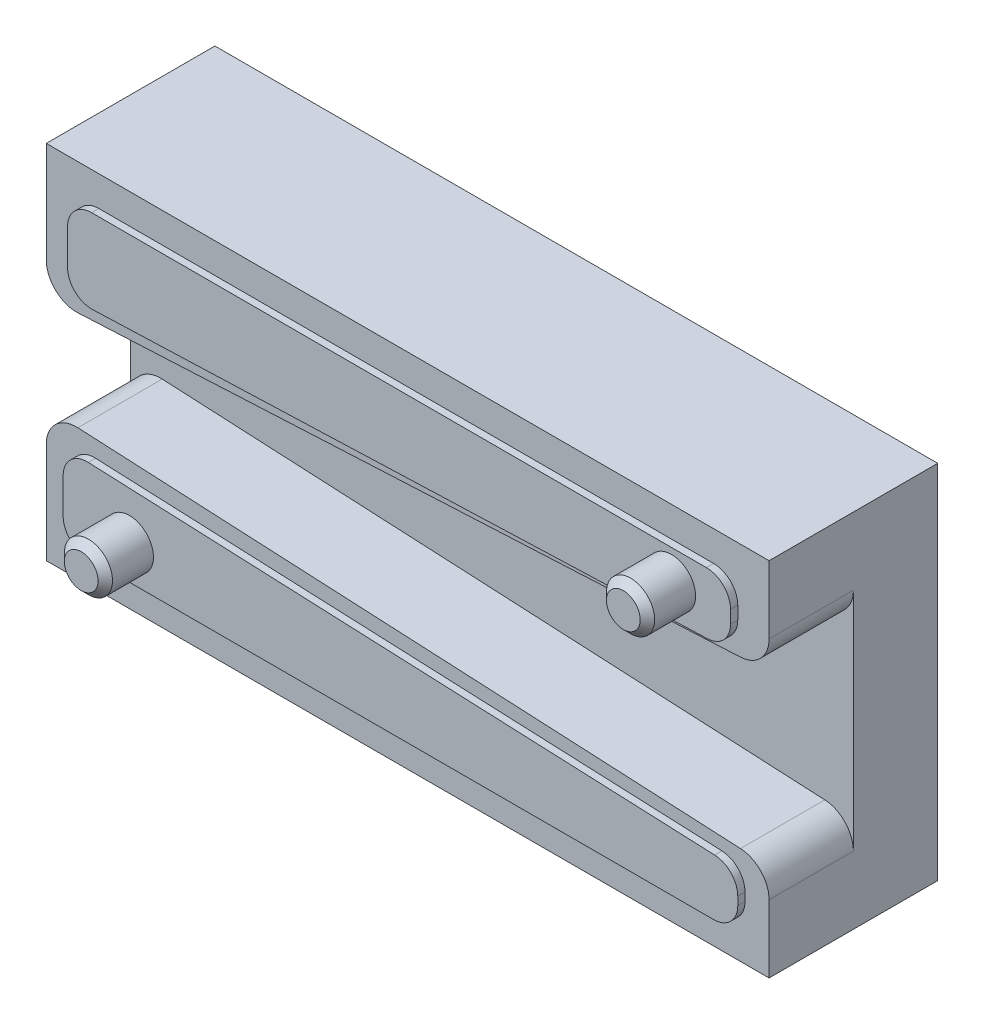
SolidWorks part; units mm, degrees
ref_plane "Front Plane" through (0, 0, 0) normal (0, 0, 1) x (1, 0, 0)
ref_plane "Top Plane" through (0, 0, 0) normal (0, 1, 0) x (1, 0, 0)
ref_plane "Right Plane" through (0, 0, 0) normal (1, 0, 0) x (0, 0, -1)
sketch "Sketch1" plane through (0, 0, 0) normal (0, 0, 1) x (1, 0, 0)
  line L1 (0, 0) -> (-76.2, 0)
  line L2 (0, 0) -> (0, -38.1)
  line L3 (0, -38.1) -> (-76.2, -38.1)
  line L4 (-76.2, 0) -> (-76.2, -38.1)
  dimension "D1" = 38.1
  dimension "D2" = 76.2
extrude "Boss-Extrude1" add sketch "Sketch1" along normal blind 17.78
sketch "Sketch2" plane through (0, 0, 17.78) normal (0, 0, 1) x (1, 0, 0)
  line L0 (-76.2, -24.13) -> (-76.2, -13.97)
  line L1 (-76.2, 0) -> (-76.2, -38.1) construction
  line L2 (0, -27.94) -> (0, -10.16)
  line L3 (0, -38.1) -> (0, 0) construction
  line L4 (-76.2, -13.97) -> (0, -10.16)
  line L5 (-76.2, -24.13) -> (0, -27.94)
  point P5 (-76.2, -19.05)
  point P10 (0, -19.05)
  dimension "D1" = 5.08
  dimension "D2" = 8.89
extrude "Cut-Extrude1" cut sketch "Sketch2" against normal blind 8.89
fillet "Fillet1" radius 3.175 4 edges at (-76.2, -24.13, 13.335) (-76.2, -13.97, 13.335) (0, -27.94, 13.335) (0, -10.16, 13.335)
sketch "Sketch3" plane through (0, 0, 17.78) normal (0, 0, 1) x (1, 0, 0)
  line L0 (-76.2, -38.1) -> (0, -38.1) construction
  line L2 (-76.2, -19.05) -> (0, -19.05) construction
  line L3 (-76.2, -10.6323) -> (-76.2, -27.4677) construction
  line L4 (0, -30.9602) -> (0, -7.1398) construction
  line L5 (-38.1, -38.1) -> (-38.1, 0) construction
  line L6 (0, 0) -> (-76.2, 0) construction
  line L7 (-9.525, -6.35) -> (-9.525, 0) construction
  circle A1 centre (-9.525, -6.35) radius 2.54
  circle A2 centre (-66.675, -31.369) radius 2.54
  dimension "D1" = 5.08
  dimension "D2" = 5.08
  dimension "D4" = 6.35
extrude "Boss-Extrude2" add sketch "Sketch3" along normal offset from surface (5.842 mm away) 23.622 up to face at (-38.1, -19.05, 0)
chamfer "Chamfer1" distance 0.762 angle 45 2 edges at (-12.065, -6.35, 23.622) (-69.215, -31.369, 23.622)
sketch "Sketch4" plane through (0, 0, 17.78) normal (0, 0, 1) x (1, 0, 0)
  line L0 (-73.66, -26.035) -> (-2.54, -29.083)
  line L1 (-2.54, -29.083) -> (-2.54, -34.925)
  line L2 (-2.54, -34.925) -> (-73.66, -34.925)
  line L3 (-73.66, -34.925) -> (-73.66, -26.035)
  line L6 (-76.2, -38.1) -> (0, -38.1) construction
  dimension "D1" = 3.175
  dimension "D4" = 8.89
  dimension "D5" = 5.842
extrude "Boss-Extrude3" add sketch "Sketch4" along normal blind 0.762
fillet "Fillet2" radius 2.54 4 edges at (-73.66, -34.925, 18.161) (-73.66, -26.035, 18.161) (-2.54, -29.083, 18.161) (-2.54, -34.925, 18.161)
sketch "Sketch5" plane through (0, 0, 17.78) normal (0, 0, 1) x (1, 0, 0)
  line L1 (-73.1926, -3.175) -> (-3.302, -3.175)
  line L2 (-73.1926, -3.175) -> (-73.1926, -12.065)
  line L3 (-73.1926, -12.065) -> (-3.302, -9.525)
  line L4 (-3.302, -3.175) -> (-3.302, -9.525)
  line L5 (0, 0) -> (-76.2, 0) construction
  dimension "D1" = 3.175
  dimension "D2" = 8.89
  dimension "D3" = 6.35
extrude "Boss-Extrude4" add sketch "Sketch5" along normal blind 0.762
fillet "Fillet3" radius 2.54 4 edges at (-3.302, -3.175, 18.161) (-3.302, -9.525, 18.161) (-73.1926, -3.175, 18.161) (-73.1926, -12.065, 18.161)
